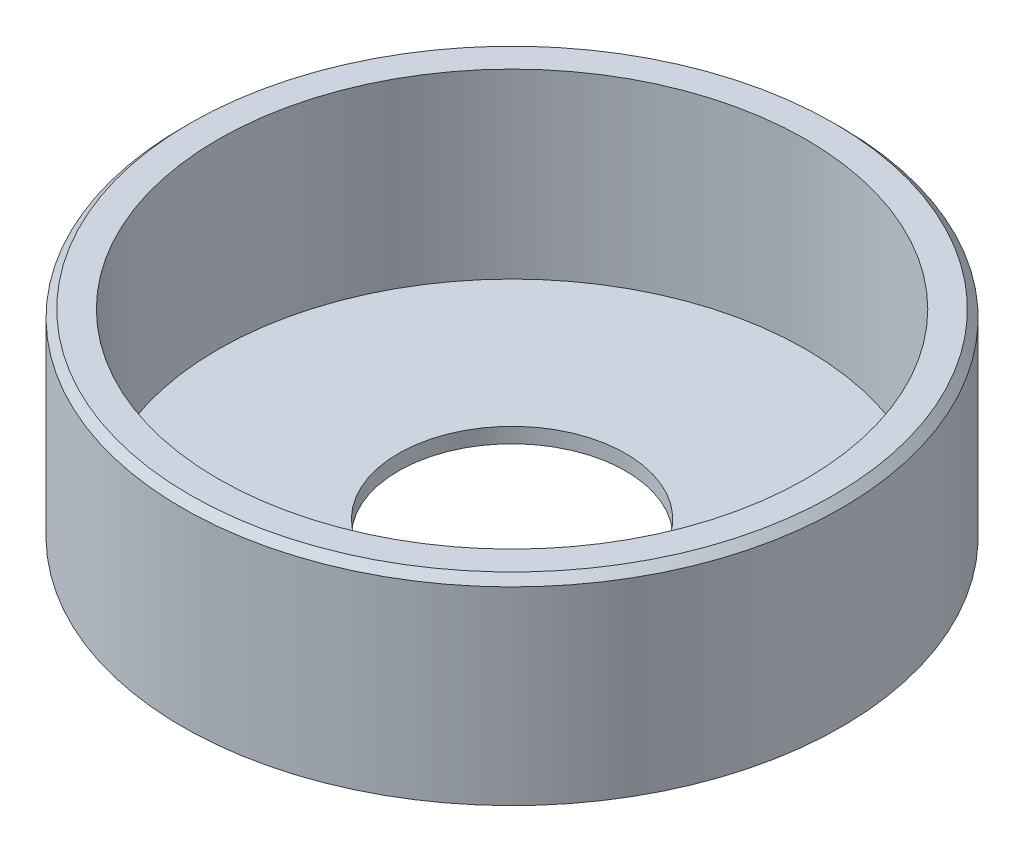
SolidWorks part; units mm, degrees
ref_plane "前视基准面" through (0, 0, 0) normal (0, 0, 1) x (1, 0, 0)
ref_plane "上视基准面" through (0, 0, 0) normal (0, 1, 0) x (1, 0, 0)
ref_plane "右视基准面" through (0, 0, 0) normal (1, 0, 0) x (0, 0, -1)
sketch "草图1" plane through (0, 0, 0) normal (0, 1, 0) x (1, 0, 0)
  circle A0 centre (0, 0) radius 43.5
extrude "凸台-拉伸1" add sketch "草图1" along normal blind 26
sketch "草图2" plane through (0, 26, 0) normal (0, 1, 0) x (1, 0, 0)
  circle A0 centre (0, 0) radius 38.8
extrude "切除-拉伸1" cut sketch "草图2" against normal blind 24
sketch "草图3" plane through (0, 2, 0) normal (0, 1, 0) x (1, 0, 0)
  circle A0 centre (0, 0) radius 15
extrude "切除-拉伸2" cut sketch "草图3" against normal through all
chamfer "倒角1" distance 1 angle 45 1 edges at (0, 26, 43.5)
